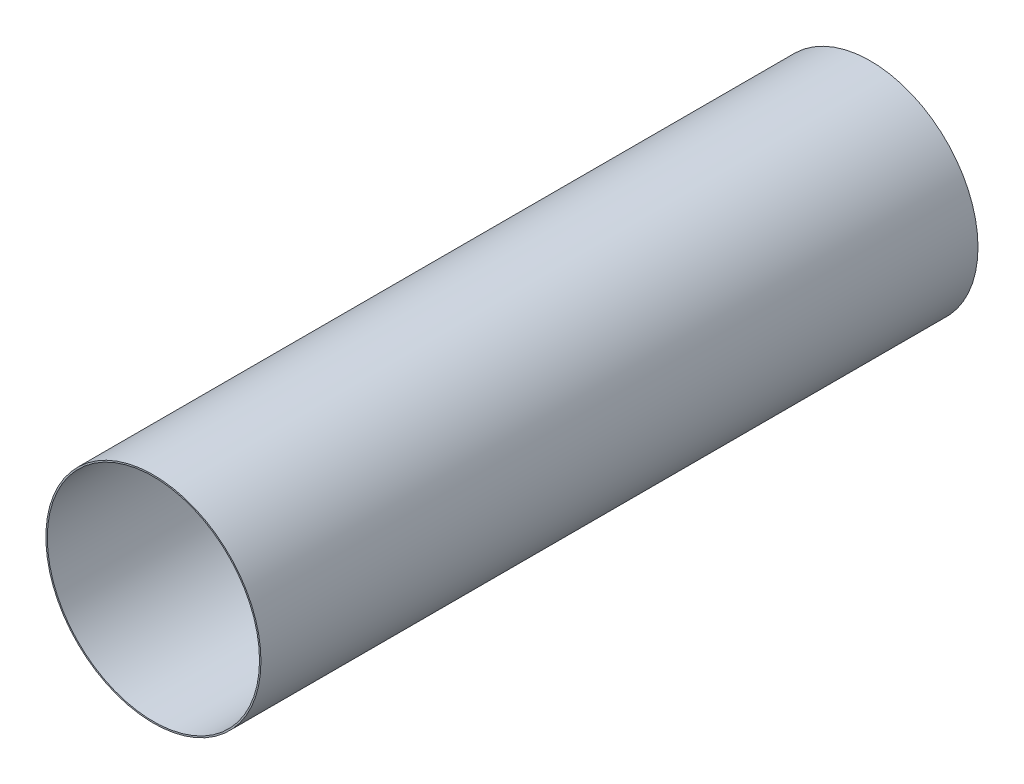
SolidWorks part; units mm, degrees
ref_plane "正面" through (0, 0, 0) normal (0, 0, 1) x (1, 0, 0)
ref_plane "平面" through (0, 0, 0) normal (0, 1, 0) x (1, 0, 0)
ref_plane "右側面" through (0, 0, 0) normal (1, 0, 0) x (0, 0, -1)
sketch "ｽｹｯﾁ1" plane through (0, 0, 0) normal (0, 0, 1) x (1, 0, 0)
  circle A0 centre (0, 0) radius 150
  dimension "D1" = 300
extrude "ﾎﾞｽ - 押し出し1" add sketch "ｽｹｯﾁ1" along normal blind 1000
shell "ｼｪﾙ1" thickness 2
